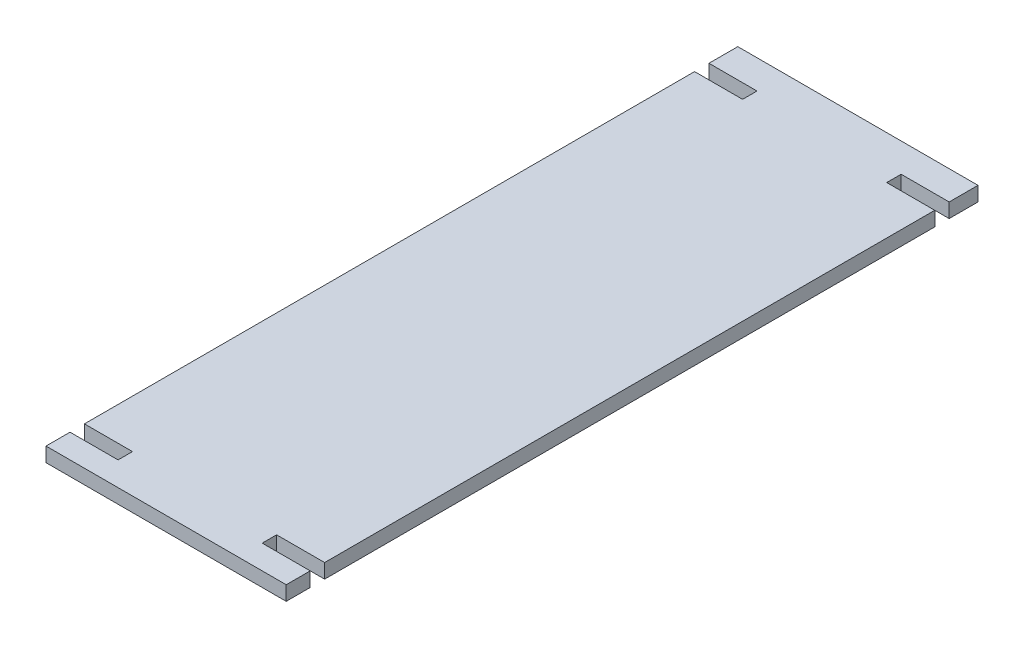
SolidWorks part; units mm, degrees
ref_plane "Front" through (0, 0, 0) normal (0, 0, 1) x (1, 0, 0)
ref_plane "Top" through (0, 0, 0) normal (0, 1, 0) x (1, 0, 0)
ref_plane "Right" through (0, 0, 0) normal (1, 0, 0) x (0, 0, -1)
sketch "Sketch1" plane through (0, 0, 0) normal (0, 1, 0) x (1, 0, 0)
  line L1 (0, 0) -> (-100, 0)
  line L2 (0, 0) -> (0, 288)
  line L3 (0, 288) -> (-100, 288)
  line L4 (-100, 0) -> (-100, 288)
  dimension "D1" = 288
  dimension "D2" = 100
extrude "Boss-Extrude1" add sketch "Sketch1" along normal blind 6
sketch "Sketch2" plane through (0, 6, 0) normal (0, 1, 0) x (1, 0, 0)
  line L0 (-100, 288) -> (-100, 0) construction
  line L1 (-100, 276) -> (-80, 276)
  line L2 (-100, 276) -> (-100, 270)
  line L3 (-100, 270) -> (-80, 270)
  line L4 (-80, 276) -> (-80, 270)
  line L5 (0, 288) -> (-100, 288) construction
  dimension "D1" = 6
  dimension "D2" = 20
  dimension "D3" = 12
extrude "Cut-Extrude1" cut sketch "Sketch2" against normal through all
pattern_linear "LPattern1" count 2 spacing 260 along (0, 0, 1) count 2 spacing 80 along (1, 0, 0) of "Cut-Extrude1"
